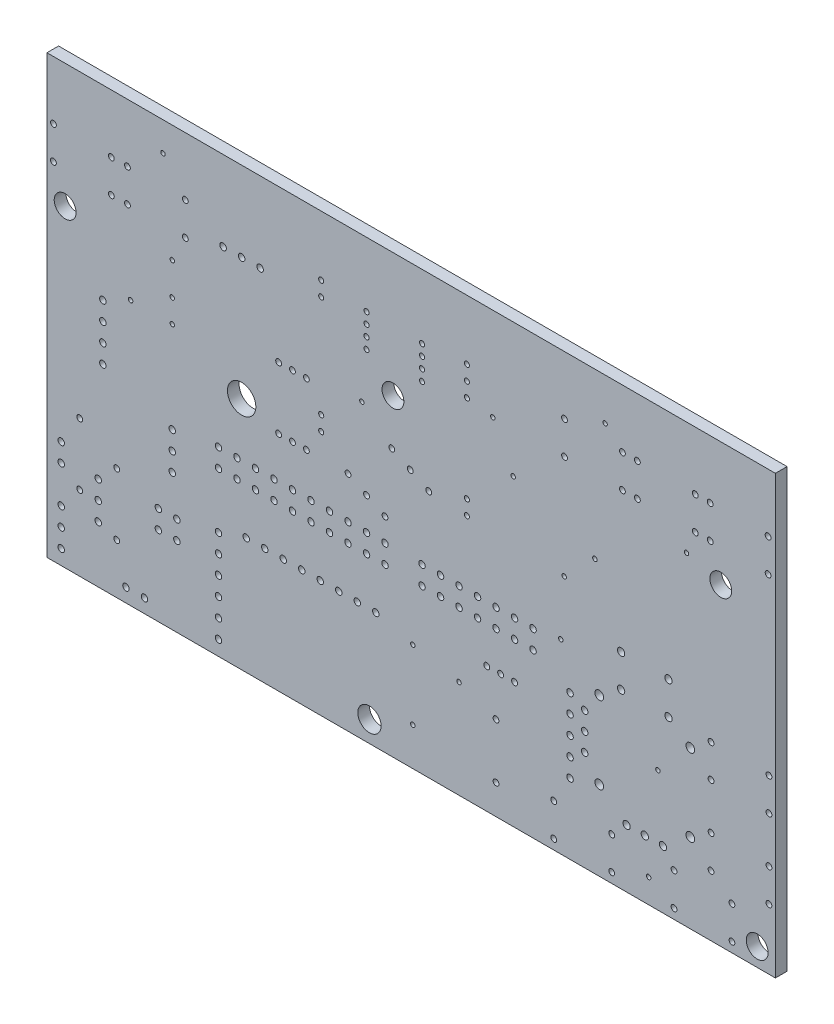
SolidWorks part; units mm, degrees
ref_plane "Front Plane" through (0, 0, 0) normal (0, 0, 1) x (1, 0, 0)
ref_plane "Top Plane" through (0, 0, 0) normal (0, 1, 0) x (1, 0, 0)
ref_plane "Right Plane" through (0, 0, 0) normal (1, 0, 0) x (0, 0, -1)
sketch "Model" plane through (0, 0, 0) normal (0, 0, 1) x (1, 0, 0)
  line L0 (440, 445) -> (540, 445)
  line L1 (540, 445) -> (540, 505)
  line L2 (540, 505) -> (440, 505)
  line L3 (440, 505) -> (440, 445)
  circle A0 centre (457.2, 481.33) radius 0.305
  circle A1 centre (451.485, 481.33) radius 0.305
  circle A2 centre (496.57, 458.47) radius 0.305
  circle A3 centre (457.2, 488.95) radius 0.305
  circle A4 centre (515.213, 482.437) radius 0.305
  circle A5 centre (516.617, 499.252) radius 0.305
  circle A6 centre (501.205, 492.256) radius 0.305
  circle A7 centre (511.007, 478.255) radius 0.305
  circle A8 centre (510.54, 470.535) radius 0.305
  circle A9 centre (455.93, 501.015) radius 0.305
  circle A10 centre (522.605, 448.31) radius 0.305
  circle A11 centre (523.875, 461.645) radius 0.305
  circle A12 centre (457.2, 484.505) radius 0.305
  circle A13 centre (490.22, 450.215) radius 0.305
  circle A14 centre (490.22, 459.74) radius 0.305
  circle A15 centre (483.235, 485.14) radius 0.305
  circle A16 centre (504, 486.651) radius 0.305
  circle A17 centre (527.8, 489.443) radius 0.305
  circle A18 centre (494.03, 467.36) radius 0.4445
  circle A19 centre (491.49, 467.36) radius 0.4445
  circle A20 centre (486.41, 467.36) radius 0.4445
  circle A21 centre (483.87, 467.36) radius 0.4445
  circle A22 centre (481.33, 467.36) radius 0.4445
  circle A23 centre (478.79, 467.36) radius 0.4445
  circle A24 centre (476.25, 467.36) radius 0.4445
  circle A25 centre (453.39, 446.886) radius 0.4445
  circle A26 centre (450.85, 446.886) radius 0.4445
  circle A27 centre (457.2, 463.714) radius 0.4445
  circle A28 centre (457.2, 466.254) radius 0.4445
  circle A29 centre (457.2, 468.794) radius 0.4445
  circle A30 centre (447.675, 479.425) radius 0.4445
  circle A31 centre (447.675, 476.885) radius 0.4445
  circle A32 centre (447.675, 474.345) radius 0.4445
  circle A33 centre (447.675, 471.805) radius 0.4445
  circle A34 centre (447.04, 457.835) radius 0.4445
  circle A35 centre (447.04, 455.295) radius 0.4445
  circle A36 centre (447.04, 452.755) radius 0.4445
  circle A37 centre (441.96, 459.74) radius 0.4445
  circle A38 centre (441.96, 457.2) radius 0.4445
  circle A39 centre (449.58, 451.875) radius 0.4
  circle A40 centre (449.58, 460.375) radius 0.4
  circle A41 centre (444.5, 463.795) radius 0.4
  circle A42 centre (444.5, 455.295) radius 0.4
  circle A43 centre (494.03, 469.9) radius 0.4445
  circle A44 centre (491.49, 469.9) radius 0.4445
  circle A45 centre (496.57, 467.36) radius 0.4445
  circle A46 centre (496.57, 469.9) radius 0.4445
  circle A47 centre (440.89, 497) radius 0.4
  circle A48 centre (440.89, 492.5) radius 0.4
  circle A49 centre (448.84, 492.5) radius 0.4
  circle A50 centre (448.84, 497) radius 0.4
  circle A51 centre (451.05, 497) radius 0.4
  circle A52 centre (451.05, 492.5) radius 0.4
  circle A53 centre (459, 492.5) radius 0.4
  circle A54 centre (459, 497) radius 0.4
  circle A55 centre (531.05, 497) radius 0.4
  circle A56 centre (531.05, 492.5) radius 0.4
  circle A57 centre (539, 492.5) radius 0.4
  circle A58 centre (539, 497) radius 0.4
  circle A59 centre (521.05, 497) radius 0.4
  circle A60 centre (521.05, 492.5) radius 0.4
  circle A61 centre (529, 492.5) radius 0.4
  circle A62 centre (529, 497) radius 0.4
  circle A63 centre (511.05, 497) radius 0.4
  circle A64 centre (511.05, 492.5) radius 0.4
  circle A65 centre (519, 492.5) radius 0.4
  circle A66 centre (519, 497) radius 0.4
  circle A67 centre (466.725, 477.23) radius 1.95
  circle A68 centre (464.185, 494.03) radius 0.45
  circle A69 centre (466.725, 494.03) radius 0.45
  circle A70 centre (469.265, 494.03) radius 0.45
  circle A71 centre (457.835, 455.93) radius 0.4445
  circle A72 centre (455.295, 455.93) radius 0.4445
  circle A73 centre (455.295, 458.47) radius 0.4445
  circle A74 centre (457.835, 458.47) radius 0.4445
  circle A75 centre (441.96, 447.04) radius 0.4445
  circle A76 centre (441.96, 449.58) radius 0.4445
  circle A77 centre (441.96, 452.12) radius 0.4445
  circle A78 centre (484.27, 447.89) radius 1.6
  circle A79 centre (485.14, 461.01) radius 0.4445
  circle A80 centre (482.6, 461.01) radius 0.4445
  circle A81 centre (480.06, 461.01) radius 0.4445
  circle A82 centre (477.52, 461.01) radius 0.4445
  circle A83 centre (474.98, 461.01) radius 0.4445
  circle A84 centre (472.44, 461.01) radius 0.4445
  circle A85 centre (469.9, 461.01) radius 0.4445
  circle A86 centre (467.36, 461.01) radius 0.4445
  circle A87 centre (471.805, 484.1) radius 0.4
  circle A88 centre (471.805, 475.6) radius 0.4
  circle A89 centre (492.42, 479.085) radius 0.4
  circle A90 centre (486.41, 473.075) radius 0.4
  circle A91 centre (489.88, 480.355) radius 0.4
  circle A92 centre (483.87, 474.345) radius 0.4
  circle A93 centre (473.71, 484.1) radius 0.4
  circle A94 centre (473.71, 475.6) radius 0.4
  circle A95 centre (475.615, 484.1) radius 0.4
  circle A96 centre (475.615, 475.6) radius 0.4
  circle A97 centre (487.34, 481.625) radius 0.4
  circle A98 centre (481.33, 475.615) radius 0.4
  circle A99 centre (491.49, 496.165) radius 0.35
  circle A100 centre (491.49, 494.665) radius 0.35
  circle A101 centre (491.49, 493.165) radius 0.35
  circle A102 centre (491.49, 491.665) radius 0.35
  circle A103 centre (483.87, 496.165) radius 0.35
  circle A104 centre (483.87, 494.665) radius 0.35
  circle A105 centre (483.87, 493.165) radius 0.35
  circle A106 centre (483.87, 491.665) radius 0.35
  circle A107 centre (497.65, 494.79) radius 0.35
  circle A108 centre (497.65, 492.79) radius 0.35
  circle A109 centre (497.65, 496.79) radius 0.35
  circle A110 centre (477.65, 494.79) radius 0.35
  circle A111 centre (477.65, 496.79) radius 0.35
  circle A112 centre (477.65, 478.79) radius 0.35
  circle A113 centre (477.65, 480.79) radius 0.35
  circle A114 centre (497.65, 480.79) radius 0.35
  circle A115 centre (497.65, 478.79) radius 0.35
  circle A116 centre (501.65, 449.065) radius 0.4
  circle A117 centre (501.65, 456.565) radius 0.4
  circle A118 centre (500.38, 462.28) radius 0.4065
  circle A119 centre (502.285, 462.28) radius 0.4065
  circle A120 centre (504.19, 462.28) radius 0.4065
  circle A121 centre (526.085, 450.85) radius 0.4
  circle A122 centre (526.085, 446.35) radius 0.4
  circle A123 centre (534.035, 446.35) radius 0.4
  circle A124 centre (534.035, 450.85) radius 0.4
  circle A125 centre (509.575, 450.85) radius 0.4
  circle A126 centre (509.575, 446.35) radius 0.4
  circle A127 centre (517.525, 446.35) radius 0.4
  circle A128 centre (517.525, 450.85) radius 0.4
  circle A129 centre (531.165, 457.835) radius 0.4
  circle A130 centre (531.165, 453.335) radius 0.4
  circle A131 centre (539.115, 453.335) radius 0.4
  circle A132 centre (539.115, 457.835) radius 0.4
  circle A133 centre (531.165, 468.63) radius 0.4
  circle A134 centre (531.165, 464.13) radius 0.4
  circle A135 centre (539.115, 464.13) radius 0.4
  circle A136 centre (539.115, 468.63) radius 0.4
  circle A137 centre (518.82, 473.18) radius 0.5
  circle A138 centre (525.32, 473.18) radius 0.5
  circle A139 centre (525.32, 468.68) radius 0.5
  circle A140 centre (518.82, 468.68) radius 0.5
  circle A141 centre (513.82, 463.73) radius 0.4445
  circle A142 centre (513.82, 461.23) radius 0.4445
  circle A143 centre (513.82, 458.73) radius 0.4445
  circle A144 centre (528.32, 466.53) radius 0.6
  circle A145 centre (515.82, 466.53) radius 0.6
  circle A146 centre (515.82, 455.93) radius 0.6
  circle A147 centre (528.32, 455.93) radius 0.6
  circle A148 centre (519.57, 452.98) radius 0.5
  circle A149 centre (522.07, 452.98) radius 0.5
  circle A150 centre (524.57, 452.98) radius 0.5
  circle A151 centre (511.81, 457.2) radius 0.4445
  circle A152 centre (511.81, 459.74) radius 0.4445
  circle A153 centre (511.81, 462.28) radius 0.4445
  circle A154 centre (511.81, 464.82) radius 0.4445
  circle A155 centre (463.55, 447.04) radius 0.4445
  circle A156 centre (463.55, 449.58) radius 0.4445
  circle A157 centre (463.55, 452.12) radius 0.4445
  circle A158 centre (463.55, 454.66) radius 0.4445
  circle A159 centre (463.55, 457.2) radius 0.4445
  circle A160 centre (463.55, 459.74) radius 0.4445
  circle A161 centre (506.73, 467.36) radius 0.4445
  circle A162 centre (504.19, 467.36) radius 0.4445
  circle A163 centre (501.65, 467.36) radius 0.4445
  circle A164 centre (499.11, 467.36) radius 0.4445
  circle A165 centre (506.73, 469.9) radius 0.4445
  circle A166 centre (504.19, 469.9) radius 0.4445
  circle A167 centre (501.65, 469.9) radius 0.4445
  circle A168 centre (499.11, 469.9) radius 0.4445
  circle A169 centre (486.41, 469.9) radius 0.4445
  circle A170 centre (483.87, 469.9) radius 0.4445
  circle A171 centre (481.33, 469.9) radius 0.4445
  circle A172 centre (478.79, 469.9) radius 0.4445
  circle A173 centre (476.25, 469.9) radius 0.4445
  circle A174 centre (473.71, 467.36) radius 0.4445
  circle A175 centre (471.17, 467.36) radius 0.4445
  circle A176 centre (468.63, 467.36) radius 0.4445
  circle A177 centre (466.09, 467.36) radius 0.4445
  circle A178 centre (463.55, 467.36) radius 0.4445
  circle A179 centre (473.71, 469.9) radius 0.4445
  circle A180 centre (471.17, 469.9) radius 0.4445
  circle A181 centre (468.63, 469.9) radius 0.4445
  circle A182 centre (466.09, 469.9) radius 0.4445
  circle A183 centre (463.55, 469.9) radius 0.4445
  circle A184 centre (487.5, 488) radius 1.5
  circle A185 centre (442.5, 488) radius 1.5
  circle A186 centre (532.5, 488) radius 1.5
  circle A187 centre (537.5, 447.5) radius 1.5
  circle A188 centre (511.81, 454.66) radius 0.4445
extrude "Boss-Extrude1" add sketch "Model" along normal blind 1.6
sketch "Sketch1" plane through (0, 0, 1.6) normal (0, 0, 1) x (1, 0, 0)
  line L0 (440.89, 497) -> (448.84, 492.5)
  line L1 (483.87, 494.665) -> (483.87, 493.165)
  line L2 (451.05, 492.5) -> (459, 497)
  line L3 (491.49, 494.665) -> (491.49, 493.165)
  line L4 (459, 492.5) -> (451.05, 497)
  line L5 (511.05, 497) -> (519, 492.5)
  line L6 (448.84, 497) -> (440.89, 492.5)
  line L7 (531.165, 468.63) -> (539.115, 464.13)
  line L8 (521.05, 492.5) -> (529, 497)
  line L9 (515.82, 466.53) -> (528.32, 455.93)
  line L10 (531.05, 497) -> (539, 492.5)
  line L11 (539.115, 457.835) -> (531.165, 453.335)
  line L12 (539, 497) -> (531.05, 492.5)
  line L13 (487.68, 459.74) -> (487.68, 445)
  line L14 (529, 492.5) -> (521.05, 497)
  line L15 (534.035, 450.85) -> (526.085, 446.35)
  line L16 (519, 497) -> (511.05, 492.5)
  line L17 (528.32, 466.53) -> (515.82, 455.93)
  line L18 (517.525, 446.35) -> (509.575, 450.85)
  line L20 (509.575, 446.35) -> (517.525, 450.85)
  line L21 (487.68, 459.74) -> (487.68, 505)
  line L22 (526.085, 450.85) -> (534.035, 446.35)
  line L24 (539.115, 453.335) -> (531.165, 457.835)
  line L25 (463.55, 459.74) -> (511.81, 459.74)
  line L26 (539.115, 468.63) -> (531.165, 464.13)
  line L28 (440, 505) -> (540, 505)
  line L29 (440, 505) -> (440, 445)
  line L30 (440, 445) -> (540, 445)
  line L31 (540, 505) -> (540, 445)
  circle A0 centre (513.55, 448.6) radius 2
  circle A1 centre (530.06, 448.6) radius 2
  circle A2 centre (535.14, 455.585) radius 2
  circle A3 centre (535.14, 466.38) radius 2
  circle A4 centre (483.87, 493.915) radius 2.5
  circle A5 centre (491.49, 493.915) radius 2.5
  circle A6 centre (535.025, 494.75) radius 2
  circle A7 centre (525.025, 494.75) radius 2
  circle A8 centre (515.025, 494.75) radius 2
  circle A9 centre (455.025, 494.75) radius 2
  circle A10 centre (444.865, 494.75) radius 2
  circle A11 centre (522.07, 461.23) radius 5
  circle A12 centre (442.5, 488) radius 3
  circle A13 centre (487.5, 488) radius 3
  circle A14 centre (532.5, 488) radius 3
  circle A15 centre (537.5, 447.5) radius 3
  circle A16 centre (484.27, 447.89) radius 3
  dimension "D1" = 5
  dimension "D2" = 5
  dimension "D3" = 4
  dimension "D4" = 4
  dimension "D5" = 4
  dimension "D6" = 4
  dimension "D7" = 4
  dimension "D8" = 4
  dimension "D9" = 4
  dimension "D10" = 4
  dimension "D11" = 4
  dimension "D12" = 10
  dimension "D14" = 6
  dimension "D13" = 6
  dimension "D15" = 6
  dimension "D16" = 6
  dimension "D17" = 6
